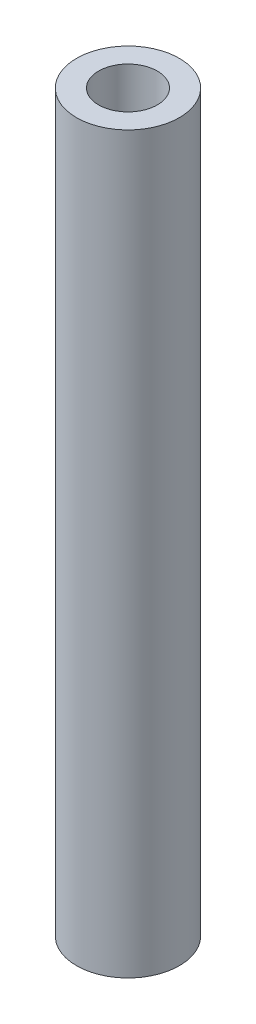
SolidWorks part; units mm, degrees
ref_plane "前视基准面" through (0, 0, 0) normal (0, 0, 1) x (1, 0, 0)
ref_plane "上视基准面" through (0, 0, 0) normal (0, 1, 0) x (1, 0, 0)
ref_plane "右视基准面" through (0, 0, 0) normal (1, 0, 0) x (0, 0, -1)
other "Configuration Table"
sketch "草图1" plane through (0, 0, 0) normal (0, 1, 0) x (1, 0, 0)
  circle A0 centre (0, 0) radius 2
  circle A1 centre (0, 0) radius 3.5
  dimension "D1" = 7
  dimension "D2" = 4
extrude "凸台-拉伸1" add sketch "草图1" along normal blind 50
